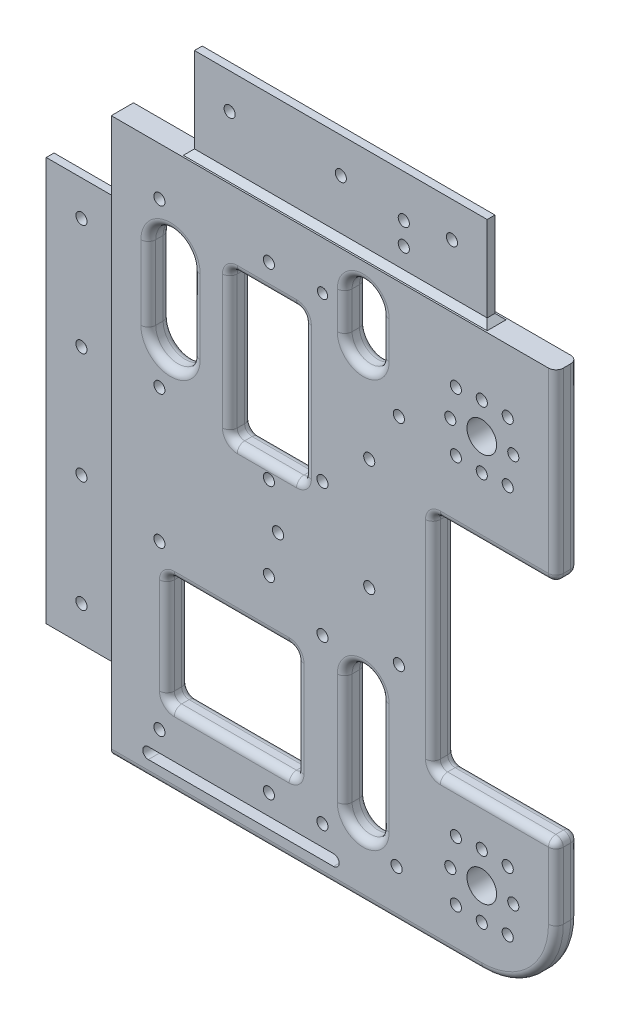
SolidWorks part; units mm, degrees
ref_plane "前视基准面" through (0, 0, 0) normal (0, 0, 1) x (1, 0, 0)
ref_plane "上视基准面" through (0, 0, 0) normal (0, 1, 0) x (1, 0, 0)
ref_plane "右视基准面" through (0, 0, 0) normal (1, 0, 0) x (0, 0, -1)
sketch "草图1" plane through (0, 0, 0) normal (0, 0, 1) x (1, 0, 0)
  line L1 (-60, 75) -> (60, 75)
  line L2 (-60, 75) -> (-60, -75)
  line L3 (-60, -75) -> (60, -75)
  line L4 (60, 75) -> (60, -75)
  line L5 (-60, 75) -> (60, -75) construction
  line L6 (-60, -75) -> (60, 75) construction
  point P0 (0, 0)
  dimension "D1" = 150
  dimension "D2" = 120
extrude "主板" add sketch "草图1" along normal mid plane 6
sketch "草图3" plane through (-60, 0, 0) normal (-1, 0, 0) x (0, 0, 1)
  line L1 (-1.05, 54.5) -> (1.05, 54.5)
  line L2 (-1.05, 54.5) -> (-1.05, -54.5)
  line L3 (-1.05, -54.5) -> (1.05, -54.5)
  line L4 (1.05, 54.5) -> (1.05, -54.5)
  line L5 (-1.05, 54.5) -> (1.05, -54.5) construction
  line L6 (-1.05, -54.5) -> (1.05, 54.5) construction
  point P0 (0, 0)
  dimension "D1" = 2.1
  dimension "D2" = 109
extrude "左插口" add sketch "草图3" along normal blind 19.5
sketch "草图2" plane through (0, 75, 0) normal (0, 1, 0) x (1, 0, 0)
  line L1 (-39.5, 1.05) -> (39.5, 1.05)
  line L2 (-39.5, 1.05) -> (-39.5, -1.05)
  line L3 (-39.5, -1.05) -> (39.5, -1.05)
  line L4 (39.5, 1.05) -> (39.5, -1.05)
  line L5 (-39.5, 1.05) -> (39.5, -1.05) construction
  line L6 (-39.5, -1.05) -> (39.5, 1.05) construction
  point P0 (0, 0)
  dimension "D1" = 2.1
  dimension "D2" = 79
extrude "上插口" add sketch "草图2" along normal blind 24.5
sketch "草图4" plane through (0, 0, 3) normal (0, 0, 1) x (1, 0, 0)
  line L0 (60, -75) -> (60, 75) construction
  line L1 (26.8, 25) -> (60, 25)
  line L2 (26.8, 25) -> (26.8, -35)
  line L3 (26.8, -35) -> (60, -35)
  line L4 (60, 25) -> (60, -35)
  line L5 (60, 75) -> (-60, 75) construction
  line L6 (-60, -75) -> (60, -75) construction
  dimension "D1" = 50
  dimension "D2" = 33.2
  dimension "D3" = 40
extrude "右轮毂" cut sketch "草图4" against normal blind 10
sketch "草图6" plane through (0, 0, 3) normal (0, 0, 1) x (1, 0, 0)
  line L0 (-79.5, 54.5) -> (-60, 54.5) construction
  line L1 (-79.5, -54.5) -> (-79.5, 54.5) construction
  line L2 (-79.5, -54.5) -> (-60, -54.5) construction
  circle A0 centre (-70, 45) radius 1.5
  circle A1 centre (-70, 15) radius 1.5
  circle A2 centre (-70, -15) radius 1.5
  circle A3 centre (-70, -45) radius 1.5
  dimension "D2" = 9.5
  dimension "D3" = 30
  dimension "D1" = 9.5
  dimension "D4" = 30
  dimension "D5" = 30
  dimension "D6" = 9.5
  dimension "D7" = 9.5
  dimension "D8" = 9.5
  dimension "D9" = 9.5
extrude "左插孔" cut sketch "草图6" against normal blind 5
sketch "草图13" plane through (0, 0, 1.05) normal (0, 0, 1) x (1, 0, 0)
  line L0 (-39.5, 99.5) -> (39.5, 99.5) construction
  line L1 (-39.5, 99.5) -> (-39.5, 75) construction
  line L2 (39.5, 99.5) -> (39.5, 75) construction
  circle A0 centre (-30, 90) radius 1.5
  circle A1 centre (0, 90) radius 1.5
  circle A2 centre (30, 90) radius 1.5
  dimension "D1" = 9.5
  dimension "D2" = 9.5
  dimension "D3" = 9.5
  dimension "D4" = 30
  dimension "D5" = 30
  dimension "D6" = 9.5
  dimension "D7" = 9.5
extrude "上插孔" cut sketch "草图13" against normal blind 10
sketch "草图9" plane through (0, 0, 3) normal (0, 0, 1) x (1, 0, 0)
  line L0 (-60, 75) -> (-60, -75) construction
  line L1 (60, 75) -> (-60, 75) construction
  line L2 (-60, -75) -> (60, -75) construction
  circle A0 centre (-17.455, 62) radius 1.5
  circle A1 centre (-17.455, 11.2) radius 1.5
  circle A2 centre (-17.455, -11.2) radius 1.5
  circle A3 centre (-17.455, -62) radius 1.5
  dimension "D1" = 42.545
  dimension "D5" = 13
  dimension "D2" = 13
  dimension "D3" = 50.8
  dimension "D4" = 0
  dimension "D6" = 50.8
extrude "拓展版" cut sketch "草图9" against normal blind 10
sketch "草图8" plane through (0, 0, 3) normal (0, 0, 1) x (1, 0, 0)
  line L0 (60, 75) -> (-60, 75) construction
  line L1 (-60, 75) -> (-60, -75) construction
  line L2 (-60, -75) -> (60, -75) construction
  circle A0 centre (-47, 62) radius 1.5
  circle A1 centre (-3, 62) radius 1.3706
  circle A2 centre (-47, 18) radius 1.4828
  circle A3 centre (-3, 18) radius 1.5
  circle A4 centre (-47, -62) radius 1.5
  circle A5 centre (-47, -18) radius 1.5
  circle A6 centre (-3, -18) radius 1.5
  circle A7 centre (-3, -62) radius 1.5
  dimension "D1" = 13
  dimension "D5" = 13
  dimension "D7" = 44
  dimension "D2" = 13
  dimension "D3" = 44
  dimension "D4" = 44
  dimension "D6" = 13
extrude "驱动板" cut sketch "草图8" against normal blind 10
sketch "草图16" plane through (0, 0, 3) normal (0, 0, 1) x (1, 0, 0)
  line L2 (60, 25) -> (26.8, 25) construction
  line L3 (26.8, 25) -> (26.8, -35) construction
  circle A0 centre (17.62, 43.5) radius 1.5
  circle A1 centre (9.62, 29.5) radius 1.5
  circle A2 centre (9.62, -0.5) radius 1.5
  circle A3 centre (17.62, -14.5) radius 1.5
  dimension "D1" = 4.5
  dimension "D2" = 17.18
  dimension "D3" = 17.18
  dimension "D4" = 30
  dimension "D5" = 14
  dimension "D6" = 8
  dimension "D7" = 8
  dimension "D8" = 14
extrude "电机" cut sketch "草图16" against normal blind 10
sketch "草图10" plane through (0, 0, 3) normal (0, 0, 1) x (1, 0, 0)
  line L0 (-60, -75) -> (60, -75) construction
  line L1 (-60, 75) -> (-60, -75) construction
  line L3 (-50, -70.5) -> (0, -70.5)
  line L4 (-50, -70.5) -> (-50, -67.5)
  line L5 (-50, -67.5) -> (0, -67.5)
  line L6 (0, -70.5) -> (0, -67.5)
  circle A0 centre (-50, -69) radius 1.5
  circle A1 centre (0, -69) radius 1.5
  dimension "D1" = 6
  dimension "D3" = 50
  dimension "D2" = 10
  dimension "D4" = 6
extrude "尾寻迹" cut sketch "草图10" against normal blind 10 contours A1 L5 A0 L3 | L4 A0 | L6 A1 | L6 A1 | L4 A0
sketch "草图11" plane through (0, 0, 3) normal (0, 0, 1) x (1, 0, 0)
  line L0 (-60, -75) -> (60, -75) construction
  line L1 (-60, 75) -> (-60, -75) construction
  line L2 (60, 75) -> (-60, 75) construction
  line L4 (3, 65) -> (13, 65)
  line L5 (3, 65) -> (3, 55)
  line L6 (3, 55) -> (13, 55)
  line L7 (13, 65) -> (13, 55)
  line L8 (3, -25) -> (13, -25)
  line L9 (3, -25) -> (3, -55)
  line L10 (3, -55) -> (13, -55)
  line L11 (13, -25) -> (13, -55)
  circle A0 centre (8, -55) radius 5
  circle A1 centre (8, 65) radius 5
  circle A2 centre (8, 55) radius 5
  circle A3 centre (8, -25) radius 5
  dimension "D1" = 20
  dimension "D3" = 10
  dimension "D4" = 10
  dimension "D6" = 68
  dimension "D2" = 68
  dimension "D5" = 30
extrude "过线孔" cut sketch "草图11" against normal blind 10 contours L4 A1 | L4 A1 | A2 L7 A1 L5 | L6 A2 | L6 A2 | L8 A3 | L8 A3 | A3 L9 A0 L11 | L10 A0 | L10 A0
sketch "草图19" plane through (0, 0, 3) normal (0, 0, 1) x (1, 0, 0)
  line L0 (60, 75) -> (-60, 75) construction
  line L1 (-50, 50) -> (-38, 50)
  line L2 (-50, 50) -> (-50, 30)
  line L3 (-50, 30) -> (-38, 30)
  line L4 (-38, 50) -> (-38, 30)
  line L5 (-45, -25) -> (-10, -25)
  line L6 (-45, -25) -> (-45, -55)
  line L7 (-45, -55) -> (-10, -55)
  line L8 (-10, -25) -> (-10, -55)
  line L9 (-60, 75) -> (-60, -75) construction
  line L10 (26.8, 25) -> (26.8, -35) construction
  line L11 (-60, -75) -> (60, -75) construction
  line L12 (60, 25) -> (26.8, 25) construction
  line L19 (-28, 55) -> (-8, 55)
  line L20 (-28, 55) -> (-28, 15)
  line L21 (-28, 15) -> (-8, 15)
  line L22 (-8, 55) -> (-8, 15)
  circle A0 centre (14.8, 15) radius 5
  circle A1 centre (-44, 50) radius 6
  circle A2 centre (-44, 30) radius 6
  dimension "D9" = 12
  dimension "D11" = 20
  dimension "D1" = 25
  dimension "D2" = 10
  dimension "D3" = 20
  dimension "D4" = 12
  dimension "D5" = 15
  dimension "D6" = 35
  dimension "D7" = 30
  dimension "D8" = 20
  dimension "D10" = 10
  dimension "D12" = 30
  dimension "D13" = 25
  dimension "D14" = 40
extrude "减重孔" cut sketch "草图19" against normal blind 10 contours L22 L3 L20 L21 | L8 L5 L6 L7 | A1 | A2
sketch "草图14" plane through (0, 0, 3) normal (0, 0, 1) x (1, 0, 0)
  line L0 (60, 75) -> (-60, 75) construction
  line L1 (60, 25) -> (60, 75) construction
  circle A0 centre (40, 50) radius 4
  circle A1 centre (48.5, 50) radius 1.5
  circle A2 centre (40, 41.5) radius 1.5
  circle A3 centre (31.5, 50) radius 1.5
  circle A4 centre (40, 58.5) radius 1.5
  circle A5 centre (33, 58) radius 1.5
  circle A6 centre (47, 58) radius 1.5
  circle A7 centre (33, 42) radius 1.5
  circle A8 centre (47, 42) radius 1.5
  dimension "D1" = 25
  dimension "D3" = 8.5
  dimension "D7" = 7
  dimension "D2" = 20
  dimension "D4" = 8.5
  dimension "D5" = 8.5
  dimension "D6" = 8.5
  dimension "D8" = 8
  dimension "D9" = 7
  dimension "D10" = 8
  dimension "D11" = 8
  dimension "D12" = 8
  dimension "D13" = 7
  dimension "D14" = 7
extrude "垂直板1" cut sketch "草图14" against normal blind 10
sketch "草图15" plane through (0, 0, 3) normal (0, 0, 1) x (1, 0, 0)
  line L0 (60, -75) -> (60, -35) construction
  line L1 (-60, -75) -> (60, -75) construction
  circle A0 centre (40, -55) radius 4
  circle A1 centre (48.5, -55) radius 1.5
  circle A2 centre (31.5, -55) radius 1.5
  circle A3 centre (40, -46.5) radius 1.5
  circle A4 centre (40, -63.55) radius 1.5
  circle A5 centre (33, -63) radius 1.5
  circle A6 centre (47, -47) radius 1.5
  circle A7 centre (33, -47) radius 1.5
  circle A8 centre (47, -63) radius 1.5
  dimension "D1" = 20
  dimension "D3" = 8.5
  dimension "D2" = 20
  dimension "D4" = 8.5
  dimension "D5" = 8.5
  dimension "D6" = 8.55
  dimension "D7" = 7
  dimension "D8" = 7
  dimension "D9" = 8
  dimension "D10" = 8
extrude "垂直板2" cut sketch "草图15" against normal blind 10
sketch "草图18" plane through (0, 0, 1.05) normal (0, 0, 1) x (1, 0, 0)
  line L0 (39.5, 99.5) -> (39.5, 75) construction
  line L1 (60, 75) -> (-60, 75) construction
  line L2 (60, 25) -> (60, 75) construction
  circle A0 centre (17, 82) radius 1.5
  circle A1 centre (17, 88) radius 1.5
  dimension "D1" = 22.5
  dimension "D2" = 7
  dimension "D3" = 22.5
  dimension "D4" = 13
  dimension "D5" = 43
  dimension "D6" = 43
extrude "二层1" cut sketch "草图18" against normal blind 10
sketch "草图17" plane through (0, 0, 3) normal (0, 0, 1) x (1, 0, 0)
  line L1 (-60, -75) -> (60, -75) construction
  line L2 (60, -75) -> (60, -35) construction
  circle A0 centre (17, -62) radius 1.5
  dimension "D1" = 43
  dimension "D2" = 13
extrude "二层2" cut sketch "草图17" against normal blind 10 contours A0
sketch "草图21" plane through (0, 0, 3) normal (0, 0, 1) x (1, 0, 0)
  line L0 (-60, 75) -> (-60, -75) construction
  line L1 (60, 75) -> (-60, 75) construction
  circle A0 centre (-15, 0) radius 1.5
  dimension "D1" = 45
  dimension "D2" = 75
extrude "底架" cut sketch "草图21" against normal blind 10
chamfer "左倒角" distance 1.5 angle 45 4 edges at (-60, -54.5, 0) (-60, 0, 1.05) (-60, 0, -1.05) (-60, 54.5, 0)
chamfer "上倒角" distance 1.5 angle 45 4 edges at (39.5, 75, 0) (0, 75, 1.05) (-39.5, 75, 0) (0, 75, -1.05)
fillet "减重孔圆角" radius 2 32 edges at (-27.5, -55, -3) (-27.5, -55, 3) (-45, -40, -3) (-45, -55, 0) (-45, -40, 3) (-50, 40, -3) (-50, 40, 3) (-10, -40, -3) (-10, -40, 3) (-10, -55, 0) (-38, 40, -3) (-38, 40, 3) (-27.5, -25, -3) (-45, -25, 0) (-27.5, -25, 3) (-10, -25, 0) (-18, 15, 3) (-18, 15, -3) (-28, 55, 0) (-8, 15, 0) (-28, 35, -3) (-28, 15, 0) (-28, 35, 3) (-18, 55, 3) (-18, 55, -3) (-8, 55, 0) (-8, 35, 3) (-8, 35, -3) (-44, 56, -3) (-44, 24, -3) (-44, 56, 3) (-44, 24, 3)
fillet "过线孔圆角" radius 2 16 edges at (8, -20, -3) (8, -20, 3) (13, -40, 3) (13, -40, -3) (8, -60, -3) (8, -60, 3) (3, -40, -3) (3, -40, 3) (8, 70, -3) (8, 70, 3) (13, 60, 3) (13, 60, -3) (8, 50, -3) (8, 50, 3) (3, 60, -3) (3, 60, 3)
fillet "右下大圆角" radius 20 1 edges at (60, -75, 0)
fillet "边缘圆角" radius 2 18 edges at (-10, -75, -3) (-10, -75, 3) (54.1421, -69.1421, -3) (54.1421, -69.1421, 3) (60, -45, -3) (60, -45, 3) (60, 50, -3) (60, 50, 3) (26.8, -5, -3) (26.8, -5, 3) (43.4, 25, -3) (26.8, 25, 0) (43.4, 25, 3) (60, 25, 0) (43.4, -35, -3) (60, -35, 0) (43.4, -35, 3) (26.8, -35, 0)
sketch "草图20" plane through (0, 0, 3) normal (0, 0, 1) x (1, 0, 0)
  line L0 (24.8, -33) -> (24.8, 23) construction
  line L1 (-25.2, 40) -> (-10.2, 40)
  line L2 (-25.2, 40) -> (-25.2, 15)
  line L3 (-25.2, 15) -> (-10.2, 15)
  line L4 (-10.2, 40) -> (-10.2, 15)
  line L5 (58, 25) -> (28.8, 25) construction
  dimension "D1" = 15
  dimension "D2" = 25
  dimension "D3" = 35
  dimension "D4" = 15
